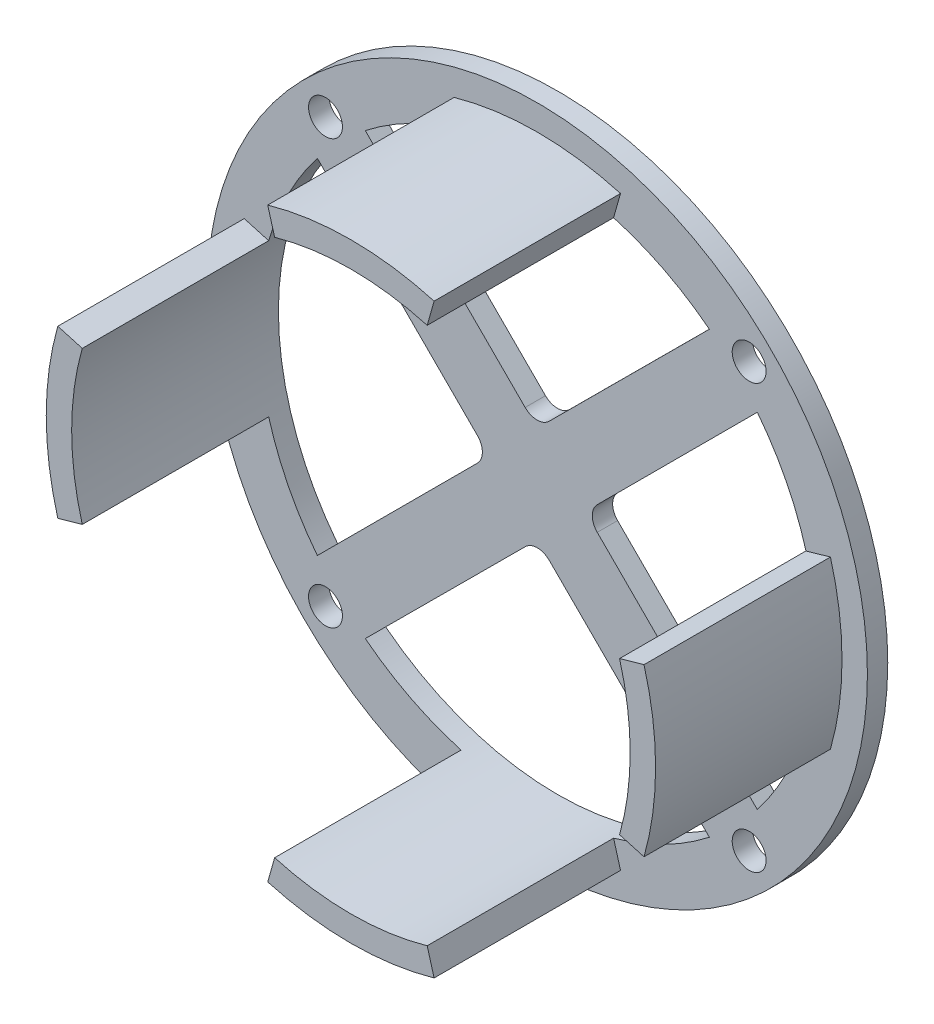
SolidWorks part; units mm, degrees
ref_plane "前视基准面" through (0, 0, 0) normal (0, 0, 1) x (1, 0, 0)
ref_plane "上视基准面" through (0, 0, 0) normal (0, 1, 0) x (1, 0, 0)
ref_plane "右视基准面" through (0, 0, 0) normal (1, 0, 0) x (0, 0, -1)
other "Configuration Table"
sketch "草图4" plane through (0, 0, 0) normal (0, 0, 1) x (1, 0, 0)
  line L0 (-10.22, 3.1897) -> (-16.584, -3.1742) construction
  line L1 (-3.2498, 12.9881) -> (-26.3827, -10.1441) construction
  line L2 (-0.4214, 10.1597) -> (-23.5543, -12.9726) construction
  line L3 (-0.4217, -10.1444) -> (-23.5541, 12.9883) construction
  line L4 (-3.2498, -12.9726) -> (-26.3824, 10.16) construction
  line L5 (-23.5543, -12.9726) -> (-0.4214, 10.1597) construction
  line L6 (-26.3827, -10.1441) -> (-3.2498, 12.9881) construction
  line L7 (-26.3824, 10.16) -> (-3.2498, -12.9726) construction
  line L8 (-23.5541, 12.9883) -> (-0.4217, -10.1444) construction
  line L9 (-0.4217, -10.1444) -> (-9.8665, -0.6993)
  line L10 (-9.8665, 0.7149) -> (-0.4214, 10.1597)
  line L11 (-3.2498, 12.9881) -> (-12.708, 3.5545)
  line L12 (-14.1213, 3.5554) -> (-23.5541, 12.9883)
  line L13 (-26.3824, 10.16) -> (-16.9376, 0.7149)
  line L14 (-16.9376, -0.6993) -> (-26.3827, -10.1441)
  line L15 (-23.5543, -12.9726) -> (-14.1082, -3.551)
  line L16 (-12.6959, -3.551) -> (-3.2498, -12.9726)
  arc A5 (-26.3824, 10.16) -> (-26.3827, -10.1441) centre (-13.4021, 0.0078) ccw
  arc A6 (-14.1082, -3.551) -> (-12.6959, -3.551) centre (-13.4021, -4.2591) cw
  arc A7 (-16.9376, 0.7149) -> (-16.9376, -0.6993) centre (-17.6447, 0.0078) cw
  arc A8 (-12.708, 3.5545) -> (-14.1213, 3.5554) centre (-13.4142, 4.2626) cw
  arc A9 (-9.8665, -0.6993) -> (-9.8665, 0.7149) centre (-9.1594, 0.0078) cw
  arc A11 (-3.2498, 12.9881) -> (-23.5541, 12.9883) centre (-13.4021, 0.0078) ccw
  arc A12 (-0.4217, -10.1444) -> (-0.4214, 10.1597) centre (-13.4021, 0.0078) ccw
  arc A13 (-23.5543, -12.9726) -> (-3.2498, -12.9726) centre (-13.4021, 0.0078) ccw
  circle A14 centre (-25.9021, 12.5078) radius 1
  circle A15 centre (-0.9021, 12.5078) radius 1
  circle A16 centre (-0.9021, -12.4922) radius 1
  circle A17 centre (-25.9021, -12.4922) radius 1
  circle A18 centre (-13.4021, 0.0078) radius 19.479
  dimension "D4" = 1
  dimension "D9" = 3
  dimension "D3" = 9
  dimension "D7" = 12.5
  dimension "D8" = 12.5
  dimension "D5" = 2
  dimension "D6" = 2
extrude "凸台-拉伸1" add sketch "草图4" along normal blind 1.2
sketch "草图5" plane through (0, 0, 1.2) normal (0, 0, 1) x (1, 0, 0)
  line L0 (-17.9021, -15.8449) -> (-18.3117, -17.2879)
  line L1 (-8.9021, -15.8449) -> (-8.4925, -17.2879)
  line L14 (-29.2548, -4.4922) -> (-30.6978, -4.9018)
  line L15 (-29.2548, 4.5078) -> (-30.6978, 4.9174)
  line L16 (-17.9021, 15.8605) -> (-18.3117, 17.3035)
  line L17 (-8.9021, 15.8605) -> (-8.4925, 17.3035)
  line L18 (2.4506, 4.5078) -> (3.8936, 4.9174)
  line L19 (2.4506, -4.4922) -> (3.8936, -4.9018)
  line L20 (-13.4021, 0.0078) -> (-13.4021, -16.4712) construction
  line L21 (-13.4021, 0.0078) -> (-18.3117, -17.2879) construction
  line L22 (-13.4021, 0.0078) -> (-8.4925, -17.2879) construction
  arc A0 (-23.5543, -12.9726) -> (-3.2498, -12.9726) centre (-13.4021, 0.0078) ccw construction
  arc A4 (-18.3117, -17.2879) -> (-8.4925, -17.2879) centre (-13.4021, 0.0078) ccw
  arc A10 (-17.9021, -15.8449) -> (-8.9021, -15.8449) centre (-13.4021, 0.0078) ccw
  arc A16 (-30.6978, 4.9174) -> (-30.6978, -4.9018) centre (-13.4021, 0.0078) ccw
  arc A17 (-29.2548, 4.5078) -> (-29.2548, -4.4922) centre (-13.4021, 0.0078) ccw
  arc A18 (-8.4925, 17.3035) -> (-18.3117, 17.3035) centre (-13.4021, 0.0078) ccw
  arc A19 (-8.9021, 15.8605) -> (-17.9021, 15.8605) centre (-13.4021, 0.0078) ccw
  arc A20 (3.8936, -4.9018) -> (3.8936, 4.9174) centre (-13.4021, 0.0078) ccw
  arc A21 (2.4506, -4.4922) -> (2.4506, 4.5078) centre (-13.4021, 0.0078) ccw
  point P0 (-17.9021, -15.8449)
  point P5 (-8.9021, -15.8449)
  dimension "D2" = 1.5
  dimension "D3" = 9
  dimension "D1" = 4
extrude "凸台-拉伸2" add sketch "草图5" along normal blind 11
